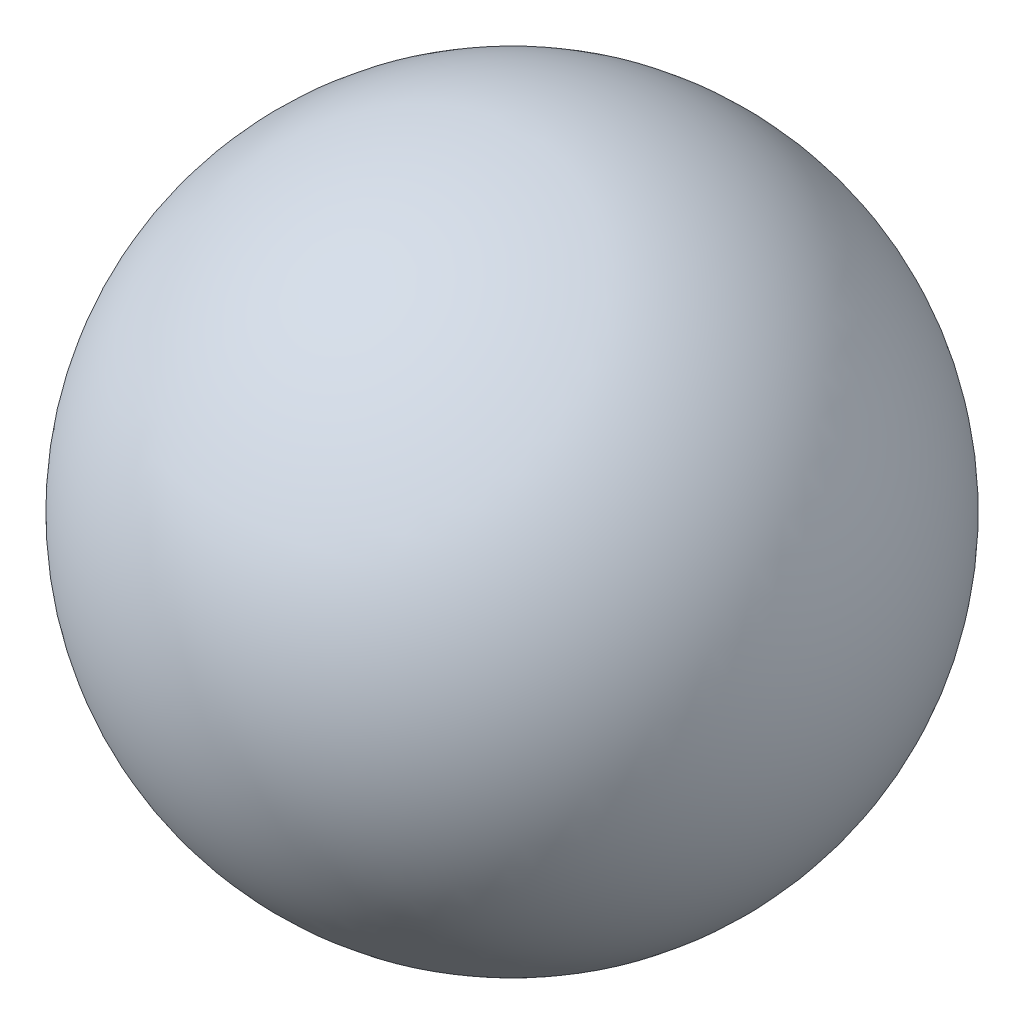
SolidWorks part; units mm, degrees
material "Plain Carbon Steel"
ref_plane "Front Plane" through (0, 0, 0) normal (0, 0, 1) x (1, 0, 0)
ref_plane "Top Plane" through (0, 0, 0) normal (0, 1, 0) x (1, 0, 0)
ref_plane "Right Plane" through (0, 0, 0) normal (1, 0, 0) x (0, 0, -1)
sketch "Sketch1" plane through (0, 0, 0) normal (0, 0, 1) x (1, 0, 0)
  line L0 (0, 17.3) -> (0, -17.3)
  line L1 (0, 41.0774) -> (0, -29.6423) construction
  arc A0 (0, -17.3) -> (0, 17.3) centre (0, 0) ccw
  dimension "D1" = 17.3
revolve "Revolve1" add sketch "Sketch1" angle 360 about L1
